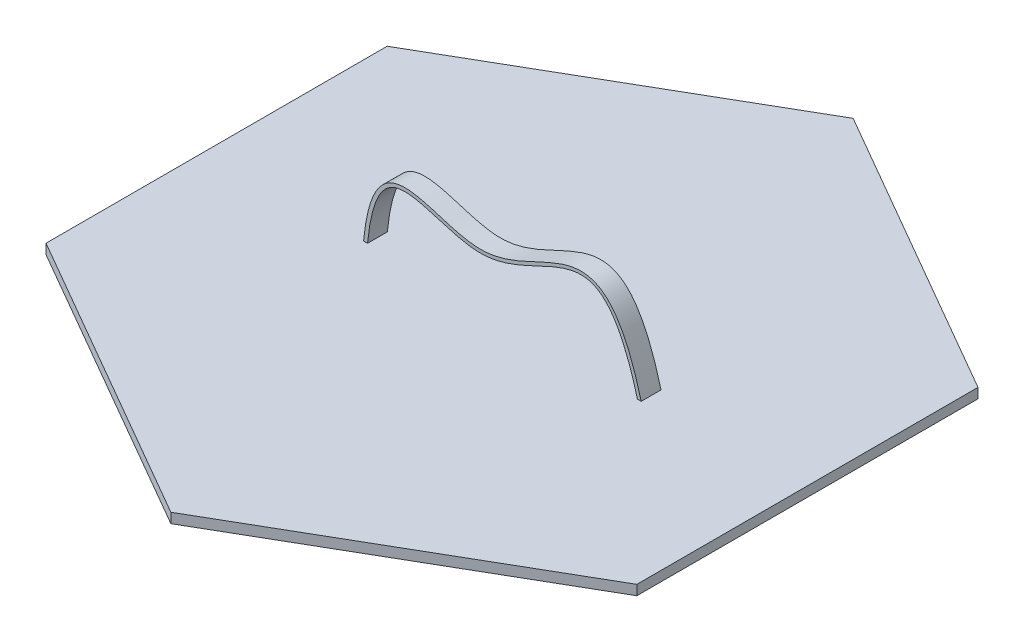
SolidWorks part; units mm, degrees
ref_plane "Front" through (0, 0, 0) normal (0, 0, 1) x (1, 0, 0)
ref_plane "Top" through (0, 0, 0) normal (0, 1, 0) x (1, 0, 0)
ref_plane "Right" through (0, 0, 0) normal (1, 0, 0) x (0, 0, -1)
sketch "Sketch1" plane through (0, 0, 0) normal (0, 1, 0) x (1, 0, 0)
  line L1 (74.4782, 43) -> (0, 86)
  line L2 (0, 86) -> (-74.4782, 43)
  line L3 (-74.4782, 43) -> (-74.4782, -43)
  line L4 (-74.4782, -43) -> (0, -86)
  line L5 (0, -86) -> (74.4782, -43)
  line L6 (74.4782, -43) -> (74.4782, 43)
  circle A0 centre (0, 0) radius 74.4782 construction
  dimension "D1" = 86
extrude "Boss-Extrude1" add sketch "Sketch1" along normal blind 2.5 contours L3 L4 L5 L6 L1 L2
sketch "Sketch3" plane through (0, 0, 0) normal (0, 0, 1) x (1, 0, 0)
  line L0 (42.5749, 2.5) -> (34.1191, 2.5) construction
  line L1 (-34.9251, 2.5) -> (-33.9201, 2.5)
  line L2 (34.1191, 2.5) -> (35.0749, 2.5)
  line L3 (-74.4782, 2.5) -> (0, 2.5) construction
  line L4 (-33.9201, 2.5) -> (-42.4251, 2.5) construction
  line L5 (33.8752, 2.5) -> (-33.8752, 2.5) construction
  line L6 (0, 0) -> (0, 5.2132) construction
  line L7 (0, 2.5) -> (0, 0) construction
  line L8 (0, 0) -> (74.4782, 0) construction
  line L9 (-4.9599, 2.5) -> (2.6774, 2.5) construction
  line L10 (0, 2.5) -> (74.4782, 2.5) construction
  spline S0 degree 3 poles (-34.9251, 2.5) (-32.1505, 30.3886) (-0.321, -3.6951) (25.0792, 39.8389) (35.0749, 2.5) knots 0 0 0 0 0.444258 1 1 1 1
  spline S2 degree 3 poles (-33.9201, 2.5) (-33.9177, 2.5241) (-33.9136, 2.5662) (-33.8662, 3.0474) (-33.7667, 3.9687) (-33.5436, 5.6975) (-33.2081, 7.727) (-32.7325, 9.8577) (-32.0076, 12.3222) (-30.9478, 14.7261) (-29.4968, 16.6566) (-27.9188, 17.8178) (-25.5841, 18.616) (-22.0271, 18.4484) (-16.9806, 17.0145) (-11.5044, 15.3014) (-6.7271, 14.4532) (-2.8894, 14.6981) (0.822, 15.4887) (5.2709, 17.2041) (10.3103, 19.6583) (15.0425, 21.7681) (18.6538, 22.6406) (21.3005, 22.5248) (23.197, 21.976) (25.0648, 20.8678) (26.9362, 19.0648) (28.7987, 16.4415) (30.3242, 13.4887) (31.52, 10.6212) (32.4025, 8.2092) (33.1266, 5.9659) (33.6653, 4.1403) (33.9318, 3.1877) (34.0722, 2.6728) (34.1019, 2.5635) (34.1191, 2.5) knots 0 0 0 0 0.0004 0.000667 0.007812 0.015625 0.03125 0.046875 0.0625 0.09375 0.125 0.15625 0.1875 0.25 0.3125 0.375 0.4375 0.46875 0.5 0.5625 0.625 0.6875 0.75 0.78125 0.8125 0.84375 0.875 0.90625 0.9375 0.953125 0.96875 0.984375 0.992188 0.998376 0.999025 1 1 1 1
extrude "Boss-Extrude3" add sketch "Sketch3" along normal mid plane 5
